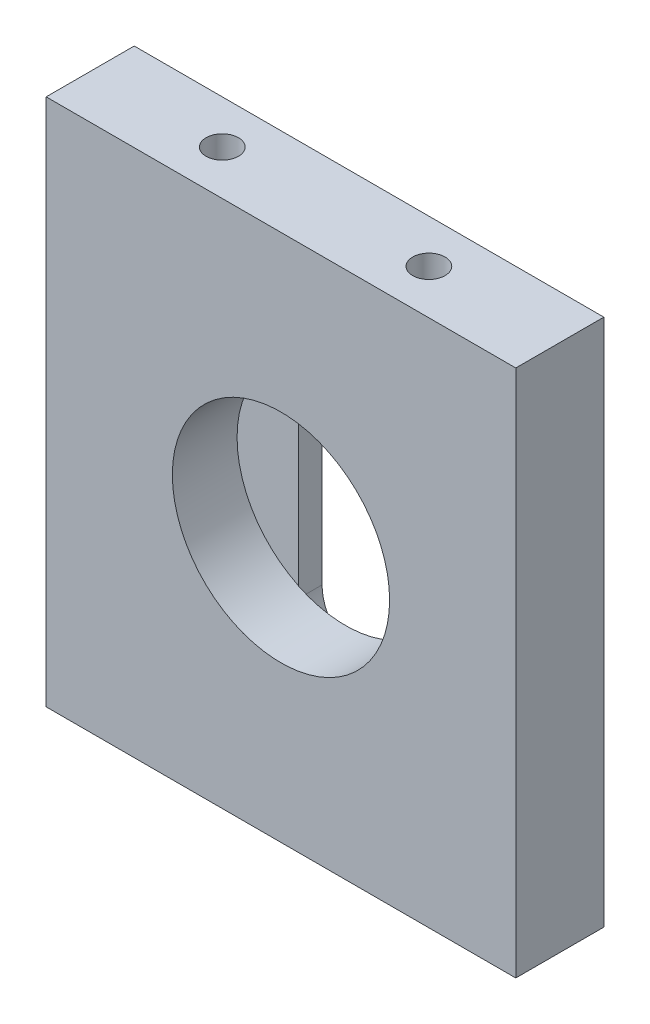
SolidWorks part; units mm, degrees
ref_plane "Front Plane" through (0, 0, 0) normal (1, 0, 0) x (0, 1, 0)
ref_plane "Top Plane" through (0, 0, 0) normal (0, 0, 1) x (0, 1, 0)
ref_plane "Right Plane" through (0, 0, 0) normal (0, 1, 0) x (-1, 0, 0)
sketch "Sketch2" plane through (0, 0, 0) normal (0, 0, 1) x (0, 1, 0)
  line L1 (0, 0) -> (114.3, 0)
  line L2 (0, 0) -> (0, 101.6)
  line L3 (0, 101.6) -> (114.3, 101.6)
  line L4 (114.3, 0) -> (114.3, 101.6)
  dimension "D1" = 114.3
  dimension "D2" = 101.6
extrude "Boss-Extrude2" add sketch "Sketch2" along normal blind 19.05
sketch "Sketch3" plane through (0, 0, 0) normal (0, -1, 0) x (1, 0, 0)
  line L0 (-101.6, 19.05) -> (-101.6, 9.652) construction
  line L1 (-101.6, 19.05) -> (-101.6, 0) construction
  line L2 (-101.6, 9.652) -> (-73.152, 9.652) construction
  line L3 (0, 19.05) -> (0, 9.652) construction
  line L4 (0, 19.05) -> (0, 0) construction
  line L5 (0, 9.652) -> (-28.448, 9.652) construction
  point P6 (-73.152, 9.652)
  point P12 (-28.448, 9.652)
  dimension "D1" = 9.398
  dimension "D2" = 28.448
hole_wizard "M8x1.0 Tapped Hole1" positions "Sketch3" profile "Sketch4" tap size "M8x1.0" standard "ANSI Metric"
sketch "Sketch4" plane through (-28.448, 0, 9.652) normal (1, 0, 0) x (0, 0, -1)
  line L0 (0, 0) -> (0, 21.153)
  line L1 (0, 21.153) -> (3.5, 19.05)
  line L2 (3.5, 19.05) -> (3.5, 0)
  line L5 (3.5, 0) -> (0, 0)
  line L10 (0, 21.153) -> (-3.5, 19.05) construction
  line L11 (0, -6.35) -> (0, 107.95) construction
  dimension "Tap Drill Dia." = 7
  dimension "Tap Drill Depth" = 19.05
  dimension "Drill Angle" = 118
cosmetic thread "Hole Thread1" parameters "D1"=16.002, "D2"=8
cosmetic thread "Hole Thread2" parameters "D1"=16.002, "D2"=8
sketch "Sketch5" plane through (0, 114.3, 0) normal (0, 1, 0) x (-1, 0, 0)
  line L0 (0, 0) -> (28.448, 0) construction
  line L1 (0, 0) -> (101.6, 0) construction
  line L2 (28.448, 0) -> (28.448, 9.398) construction
  line L3 (101.6, 0) -> (73.152, 0) construction
  line L4 (73.152, 0) -> (73.152, 9.398) construction
  point P10 (28.448, 9.398)
  point P11 (73.152, 9.398)
  dimension "D1" = 28.448
  dimension "D2" = 9.398
hole_wizard "M8x1.0 Tapped Hole2" positions "Sketch5" profile "Sketch6" tap size "M8x1.0" standard "ANSI Metric"
sketch "Sketch6" plane through (-73.152, 114.3, 9.398) normal (1, 0, 0) x (0, 0, 1)
  line L0 (0, 0) -> (0, 21.153)
  line L1 (0, 21.153) -> (3.5, 19.05)
  line L2 (3.5, 19.05) -> (3.5, 0)
  line L5 (3.5, 0) -> (0, 0)
  line L10 (0, 21.153) -> (-3.5, 19.05) construction
  line L11 (0, -6.35) -> (0, 107.95) construction
  dimension "Tap Drill Dia." = 7
  dimension "Tap Drill Depth" = 19.05
  dimension "Drill Angle" = 118
cosmetic thread "Hole Thread3" parameters "D1"=16.002, "D2"=8
cosmetic thread "Hole Thread4" parameters "D1"=16.002, "D2"=8
sketch "Sketch7" plane through (0, 0, 19.05) normal (0, 0, 1) x (1, 0, 0)
  line L0 (-101.6, 57.15) -> (0, 57.15) construction
  line L1 (-101.6, 114.3) -> (-101.6, 0) construction
  line L2 (0, 0) -> (0, 114.3) construction
  circle A0 centre (-50.8, 57.15) radius 23.5
  dimension "D1" = 47
extrude "Cut-Extrude1" cut sketch "Sketch7" against normal blind 14
sketch "Sketch8" plane through (0, 0, 0) normal (0, 0, -1) x (1, 0, 0)
  line L0 (-50.8, -114.3) -> (-50.8, -80.65) construction
  line L1 (0, -114.3) -> (-101.6, -114.3) construction
  line L2 (-50.8, 0) -> (-50.8, -33.65) construction
  line L3 (-101.6, 0) -> (0, 0) construction
  line L5 (-50.8, -33.65) -> (-50.8, -80.65) construction
  line L6 (-40.64, -33.65) -> (-40.64, -80.65)
  line L7 (-60.96, -33.65) -> (-60.96, -80.65)
  circle A0 centre (-50.8, -57.15) radius 23.5 construction
  arc A1 (-40.64, -33.65) -> (-60.96, -33.65) centre (-50.8, -33.65) ccw
  arc A2 (-60.96, -80.65) -> (-40.64, -80.65) centre (-50.8, -80.65) ccw
  point P11 (-50.8, -57.15)
  point P14 (-50.8, -33.65)
  point P19 (-50.8, -80.65)
  dimension "D1" = 20.32
  dimension "D2" = 67.32
extrude "Cut-Extrude5" cut sketch "Sketch8" against normal blind 5.08
